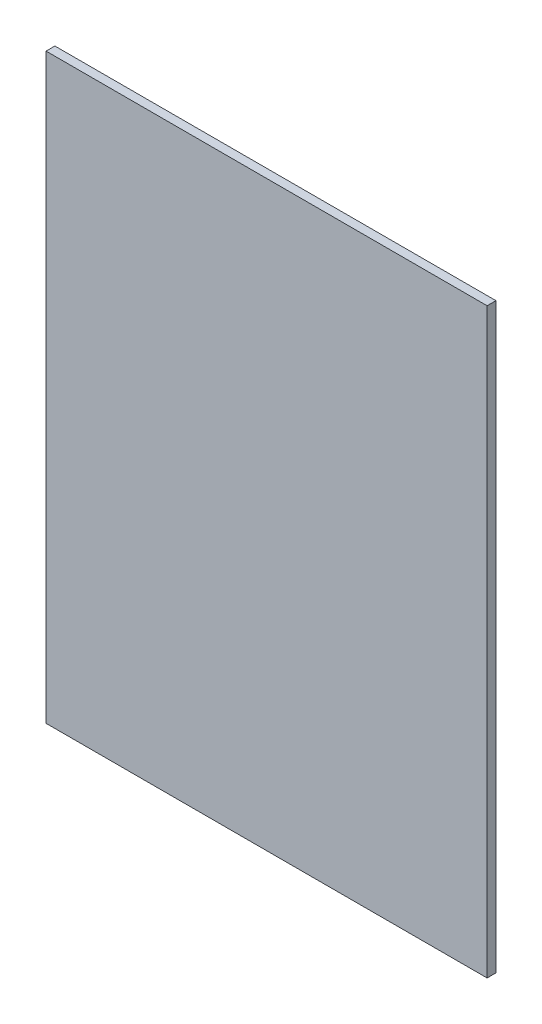
SolidWorks part; units mm, degrees
ref_plane "前视基准面" through (0, 0, 0) normal (0, 0, 1) x (1, 0, 0)
ref_plane "上视基准面" through (0, 0, 0) normal (0, 1, 0) x (1, 0, 0)
ref_plane "右视基准面" through (0, 0, 0) normal (1, 0, 0) x (0, 0, -1)
sketch "草图1" plane through (0, 0, 0) normal (0, 0, 1) x (1, 0, 0)
  line L1 (-31.3694, 26.1592) -> (18.6306, 26.1592)
  line L2 (-31.3694, 26.1592) -> (-31.3694, -39.8408)
  line L3 (-31.3694, -39.8408) -> (18.6306, -39.8408)
  line L4 (18.6306, 26.1592) -> (18.6306, -39.8408)
  dimension "D1" = 50
  dimension "D2" = 66
extrude "凸台-拉伸1" add sketch "草图1" along normal blind 1
